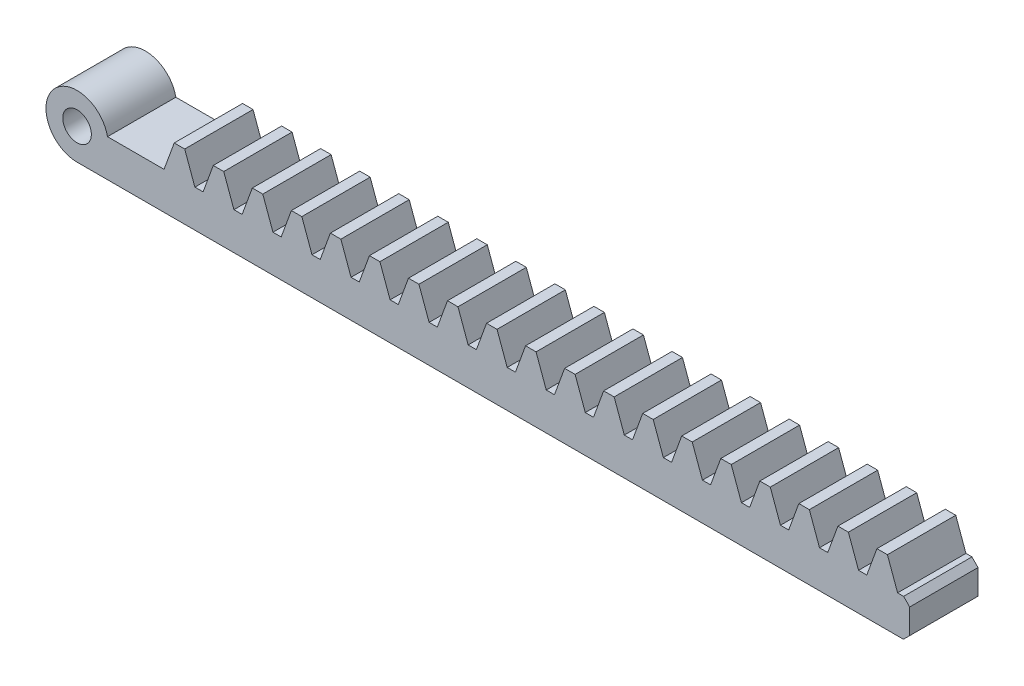
SolidWorks part; units mm, degrees
ref_plane "前视基准面" through (0, 0, 0) normal (0, 0, 1) x (1, 0, 0)
ref_plane "上视基准面" through (0, 0, 0) normal (0, 1, 0) x (1, 0, 0)
ref_plane "右视基准面" through (0, 0, 0) normal (1, 0, 0) x (0, 0, -1)
sketch "草图1" plane through (0, 0, 0) normal (0, 0, 1) x (1, 0, 0)
  line L1 (0, 0) -> (60, 0)
  line L2 (0, 0) -> (0, -3)
  line L3 (0, -3) -> (60, -3)
  line L4 (60, 0) -> (60, -3)
  dimension "D1" = 3
  dimension "L" = 60
extrude "拉伸1" add sketch "草图1" along normal blind 5.5
sketch "草图2" plane through (0, 0, 5.5) normal (0, 0, 1) x (1, 0, 0)
  line L0 (0, 0) -> (0.8189, 2.25)
  line L1 (0.8189, 2.25) -> (1.6618, 2.25)
  line L2 (1.6618, 2.25) -> (2.4807, 0)
  line L3 (60, 0) -> (0, 0) construction
  line L4 (0, 0) -> (2.4807, 0)
  line L5 (0.455, 1.25) -> (2.0258, 1.25) construction
  dimension "D2" = 70
  dimension "alpha" = 110
  dimension "ha" = 1
  dimension "hf" = 1.25
  dimension "S" = 1.5708
extrude "拉伸2" add sketch "草图2" against normal up to surface (5.5 mm away) up to face at (30, -1.5, 0)
pattern_linear "阵列(线性)1" count 19 spacing 3.1416 along (1, 0, 0) of "拉伸2"
sketch "草图3" plane through (0, 0, 0) normal (0, 0, -1) x (-1, 0, 0)
  line L0 (0, -3) -> (-60, -3) construction
  line L1 (-3.1416, 0) -> (-2.4807, 0) construction
  line L6 (-32.3969, -0.5) -> (49967.6031, -0.5) construction
  line L10 (7, -3) -> (0, -3)
  line L11 (0, -3) -> (0, 0)
  line L12 (0, 0) -> (4.5505, 0)
  circle A2 centre (7, -0.5) radius 1.15
  arc A3 (7, -3) -> (4.5505, 0) centre (7, -0.5) ccw
  dimension "D1" = 7
  dimension "D4" = 2.3
  dimension "D5" = 2.5
  dimension "D3" = 2.5
sketch "草图4" plane through (0, 0, 0) normal (-1, 0, 0) x (0, 0, 1)
  line L1 (5.5, 0) -> (0, 0)
  line L2 (5.5, 0) -> (5.5, -3)
  line L3 (5.5, -3) -> (0, -3)
  line L4 (0, 0) -> (0, -3)
extrude "凸台-拉伸1" add sketch "草图3" against normal blind 5.5
sketch "草图5" plane through (0, 0, 0) normal (0, 0, -1) x (-1, 0, 0)
  line L0 (-59.5147, 0) -> (-60, -0.5)
  line L1 (-60, -3) -> (-60, 0) construction
  line L2 (-60, -0.5) -> (-60, 0)
  line L3 (-60, 0) -> (-59.5147, 0)
  line L4 (-60, -3) -> (-60, -2.5)
  line L5 (-60, -2.5) -> (-59.5, -3)
  line L6 (7, -3) -> (-60, -3) construction
  line L7 (-59.5, -3) -> (-60, -3)
  line L8 (-60, 0) -> (-59.0294, 0) construction
  dimension "D1" = 0.5
  dimension "D2" = 0.5
  dimension "D3" = 45
extrude "切除-拉伸2" cut sketch "草图5" against normal blind 6
equation "\"d\"=\"S@草图2\" * 2"
equation "\"z\"= int(  \"L@草图1\" / (  \"S@草图2\" * 2 ) + 0.5 )"
